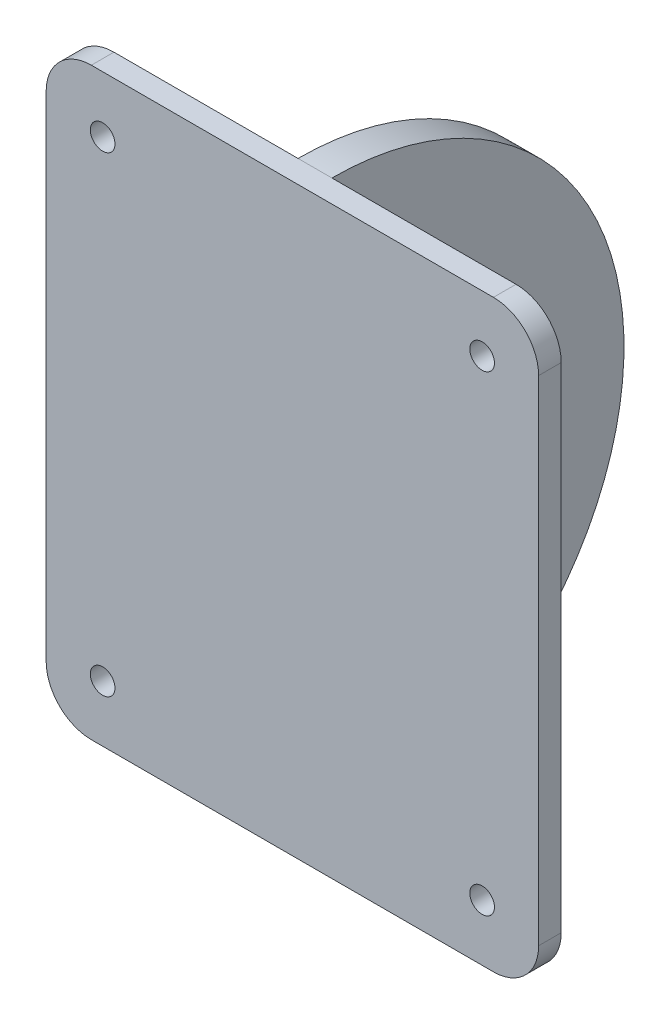
SolidWorks part; units mm, degrees
material "PE High Density"
ref_plane "Front Plane" through (0, 0, 0) normal (0, 0, 1) x (1, 0, 0)
ref_plane "Top Plane" through (0, 0, 0) normal (0, 1, 0) x (1, 0, 0)
ref_plane "Right Plane" through (0, 0, 0) normal (1, 0, 0) x (0, 0, -1)
sketch "Sketch1" plane through (0, 0, 0) normal (0, 0, 1) x (1, 0, 0)
  line L1 (-21.799, 25.8583) -> (21.799, 25.8583)
  line L2 (-21.799, 25.8583) -> (-21.799, -25.8583)
  line L3 (-21.799, -25.8583) -> (21.799, -25.8583)
  line L4 (21.799, 25.8583) -> (21.799, -25.8583)
  line L5 (-21.799, 25.8583) -> (21.799, -25.8583) construction
  line L6 (-21.799, -25.8583) -> (21.799, 25.8583) construction
  point P0 (0, 0)
  dimension "D1" = 51.7166
  dimension "D2" = 43.598
extrude "Boss-Extrude1" add sketch "Sketch1" along normal blind 2
fillet "Fillet1" radius 4 4 edges at (-21.799, -25.8583, 1) (21.799, -25.8583, 1) (-21.799, 25.8583, 1) (21.799, 25.8583, 1)
sketch "Sketch2" plane through (0, 0, 2) normal (0, 0, 1) x (1, 0, 0)
  line L0 (17.799, 25.8583) -> (-17.799, 25.8583) construction
  line L1 (-21.799, 21.8583) -> (-21.799, -21.8583) construction
  line L2 (21.799, -21.8583) -> (21.799, 21.8583) construction
  line L3 (-17.799, -25.8583) -> (17.799, -25.8583) construction
  circle A0 centre (-16.799, 20.8583) radius 1.0922
  circle A1 centre (16.799, 20.8583) radius 1.0922
  circle A2 centre (-16.799, -20.8583) radius 1.0922
  circle A3 centre (16.799, -20.8583) radius 1.0922
  dimension "D1" = 2.1844
  dimension "D2" = 2.1844
  dimension "D3" = 2.1844
  dimension "D4" = 2.1844
  dimension "D5" = 5
  dimension "D6" = 5
  dimension "D7" = 5
  dimension "D8" = 5
  dimension "D9" = 5
  dimension "D10" = 5
  dimension "D11" = 5
  dimension "D12" = 5
extrude "Cut-Extrude1" cut sketch "Sketch2" against normal blind 2
cosmetic thread "Cosmetic Thread1" parameters "D2"=3.1844
cosmetic thread "Cosmetic Thread2" parameters "D2"=3.1844
cosmetic thread "Cosmetic Thread3" parameters "D2"=3.1844
cosmetic thread "Cosmetic Thread4" parameters "D2"=3.1844
sketch "Sketch5" plane through (0, 0, 0) normal (1, 0, 0) x (0, 0, -1)
  line L0 (0, 25.8583) -> (0, -25.8583) construction
  line L1 (0, 25.8583) -> (0, -25.8583)
  arc A0 (0, -25.8583) -> (0, 25.8583) centre (0, 0) ccw
  dimension "D1" = 51.7166
extrude "Boss-Extrude2" add sketch "Sketch5" along normal mid plane 3
sketch "Sketch6" plane through (1.5, 0, 0) normal (1, 0, 0) x (0, 0, -1)
  line L0 (0, -21.8583) -> (0, 21.8583) construction
  line L1 (0, -25.8583) -> (-2, -25.8583) construction
  circle A0 centre (10.61, 0) radius 5
  dimension "D2" = 10
  dimension "D1" = 10.61
  dimension "D3" = 25.8583
extrude "Cut-Extrude2" cut sketch "Sketch6" against normal up to next
equation "\"userHeight\" = 1750mm'Users height"
equation "\"fin_hole_radius\"= 10mm'Fin hole radius"
equation "\"fin_thickness\"=3.00000000"
equation "\"D1\"= \"fin_thickness\""
equation "\"D2@Sketch6\"=\"fin_hole_radius\""
equation "\"D1@Boss-Extrude2\"=\"fin_thickness\""
equation "\"fin_platform_width\" = 43.598"
equation "\"D2@Sketch1\"=\"fin_platform_width\""
equation "\"fin_platform_height\" = 51.7166"
equation "\"D1@Sketch1\"=\"fin_platform_height\""
equation "\"hole_position_y\"= 25 * \"fin_platform_height\" / 50'Fin platform position y"
equation "\"D3@Sketch6\"=\"hole_position_y\""
equation "\"D1@Sketch5\"=\"fin_platform_height\""
equation "\"shell_outer_radius\"= 86.723"
equation "\"partial_sidebar_length\"=248.75000000"
equation "\"shell_length\"=133.89441469"
